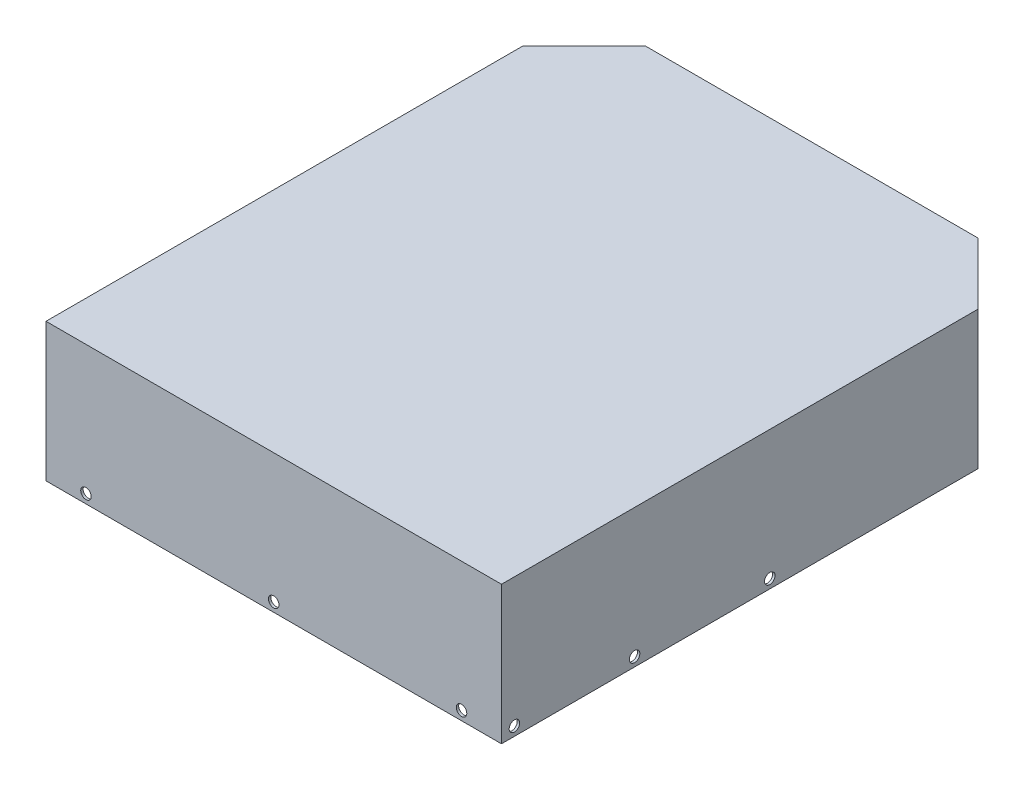
SolidWorks part; units mm, degrees
ref_plane "Front" through (0, 0, 0) normal (0, 0, 1) x (1, 0, 0)
ref_plane "Top" through (0, 0, 0) normal (0, 1, 0) x (1, 0, 0)
ref_plane "Right" through (0, 0, 0) normal (1, 0, 0) x (0, 0, -1)
sketch "Sketch1" plane through (0, 0, 0) normal (0, 1, 0) x (1, 0, 0)
  line L0 (0, -29.7406) -> (0, 446.9421) construction
  line L1 (-151.6, 0) -> (151.6, 0)
  line L2 (-151.6, 0) -> (-151.6, 358.2)
  line L3 (-151.6, 358.2) -> (151.6, 358.2)
  line L4 (151.6, 0) -> (151.6, 358.2)
  dimension "D1" = 303.2
  dimension "D2" = 358.2
extrude "Boss-Extrude1" add sketch "Sketch1" along normal blind 92
chamfer "Chamfer1" distance 41 angle 45 2 edges at (-151.6, 46, -358.2) (151.6, 46, -358.2)
shell "Shell1" thickness 1.6
hole_wizard "Ø7.0 (7) Diameter Hole1" positions "Sketch3" profile "Sketch2" hole size "Ø7.0" standard "JIS"
sketch "Sketch3" plane through (0, 0, 0) normal (0, 0, 1) x (1, 0, 0)
  line L0 (0, -30.7236) -> (0, 124.3915) construction
  line L3 (-151.6, 0) -> (151.6, 0) construction
  point P0 (-125, 6)
  point P1 (0, 6)
  point P3 (125, 6)
  dimension "D1" = 250
  dimension "D2" = 6
sketch "Sketch2" plane through (-125, 6, 0) normal (1, 0, 0) x (0, -1, 0)
  line L0 (0, 0) -> (0, 1.6)
  line L1 (0, 1.6) -> (3.5, 1.6)
  line L2 (3.5, 1.6) -> (3.5, 0)
  line L5 (3.5, 0) -> (0, 0)
  line L11 (0, -6.35) -> (0, 107.95) construction
  dimension "Thru Hole Dia." = 7
  dimension "Thru Hole Depth" = 1.6
hole_wizard "Ø7.0 (7) Diameter Hole2" positions "Sketch5" profile "Sketch4" hole size "Ø7.0" standard "JIS" end condition through all
sketch "Sketch5" plane through (-151.6, 0, 0) normal (-1, 0, 0) x (0, 0, 1)
  line L0 (0, -30.7236) -> (0, 124.3915) construction
  point P0 (-8.6, 6)
  point P4 (-88.6, 6)
  point P6 (-178.6, 6)
  dimension "D1" = 8.6
  dimension "D2" = 80
  dimension "D3" = 90
sketch "Sketch4" plane through (-151.6, 6, -8.6) normal (0, 1, 0) x (0, 0, 1)
  line L0 (0, 0) -> (0, 303.2)
  line L1 (0, 303.2) -> (3.5, 303.2)
  line L2 (3.5, 303.2) -> (3.5, 0)
  line L5 (3.5, 0) -> (0, 0)
  line L11 (0, -6.35) -> (0, 107.95) construction
  dimension "Thru Hole Dia." = 7
  dimension "Thru Hole Depth" = 303.2
